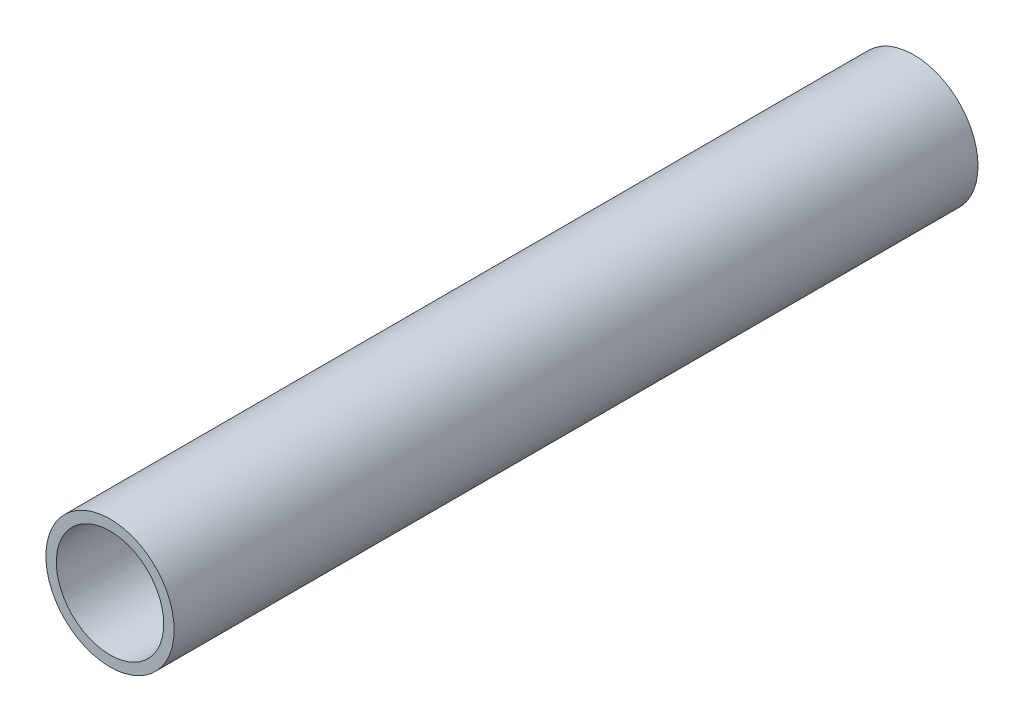
SolidWorks part; units mm, degrees
ref_plane "Front Plane" through (0, 0, 0) normal (0, 0, 1) x (1, 0, 0)
ref_plane "Top Plane" through (0, 0, 0) normal (0, 1, 0) x (1, 0, 0)
ref_plane "Right Plane" through (0, 0, 0) normal (1, 0, 0) x (0, 0, -1)
sketch "Esquisse1" plane through (0, 0, 0) normal (0, 0, 1) x (1, 0, 0)
  circle A0 centre (0, 0) radius 5.525
  circle A1 centre (0, 0) radius 4.625
  dimension "D1" = 9.25
  dimension "D2" = 11.05
extrude "Boss.-Extru.1" add sketch "Esquisse1" along normal blind 69.24
